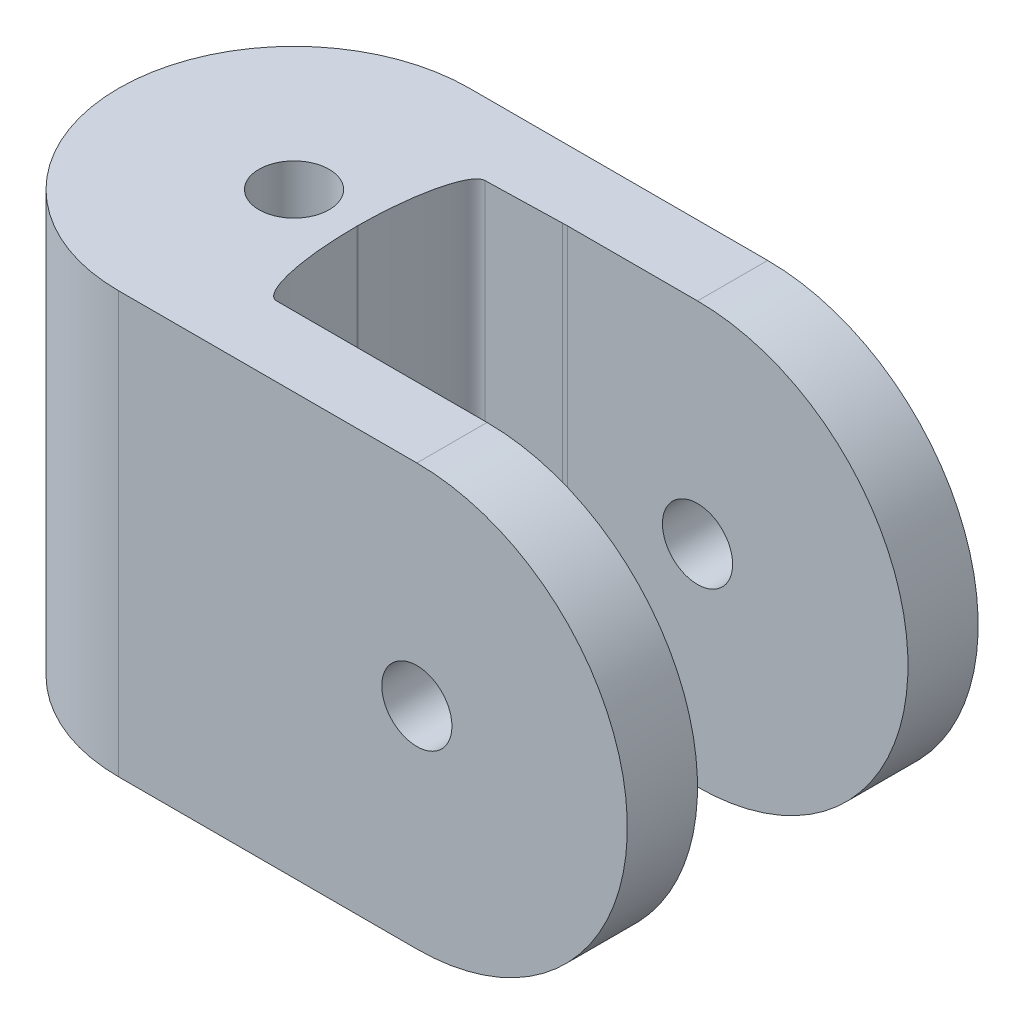
SolidWorks part; units mm, degrees
ref_plane "Front Plane" through (0, 0, 0) normal (0, 0, 1) x (1, 0, 0)
ref_plane "Top Plane" through (0, 0, 0) normal (0, 1, 0) x (1, 0, 0)
ref_plane "Right Plane" through (0, 0, 0) normal (1, 0, 0) x (0, 0, -1)
sketch "Sketch1" plane through (0, 0, 0) normal (0, 1, 0) x (1, 0, 0)
  circle A0 centre (0, 0) radius 125
  circle A1 centre (0, 0) radius 25
  dimension "D1" = 250
extrude "Boss-Extrude1" add sketch "Sketch1" along normal blind 300
ref_plane "Plane1" through (0, 0, 0) normal (0, 0, 1) x (1, 0, 0)
sketch "Sketch2" plane through (0, 0, 0) normal (0, 0, 1) x (1, 0, 0)
  line L0 (0, 300) -> (0, 0) construction
  line L1 (125, 300) -> (-125, 300) construction
  line L2 (0, 300) -> (425, 300) construction
  line L3 (425, 300) -> (425, 0) construction
  line L4 (425, 0) -> (0, 0) construction
  line L5 (0, 150) -> (425, 150) construction
  line L6 (0, 300) -> (0, 0)
  line L7 (0, 300) -> (212.5, 300)
  line L8 (0, 0) -> (212.5, 0)
  circle A0 centre (212.5, 150) radius 25
  arc A1 (212.5, 0) -> (212.5, 300) centre (212.5, 150) ccw
  dimension "D1" = 425
extrude "Boss-Extrude2" add sketch "Sketch2" along normal mid plane 250
sketch "Sketch4" plane through (0, 0, 0) normal (0, 0, 1) x (1, 0, 0)
  line L0 (0, 300) -> (0, 0)
  line L1 (0, 0) -> (212.5, 0)
  line L2 (0, 300) -> (212.5, 300)
  line L3 (3.7723, 300) -> (3.7723, 0)
  line L4 (3.7723, 0) -> (150, 0)
  line L5 (3.7723, 300) -> (150, 300)
  arc A0 (212.5, 0) -> (212.5, 300) centre (212.5, 150) ccw construction
  arc A1 (212.5, 0) -> (212.5, 300) centre (212.5, 150) ccw
  arc A2 (150, 0) -> (150, 300) centre (212.5, 150) ccw
extrude "Cut-Extrude2" cut sketch "Sketch4" against normal mid plane 150 contours L4 A2 A1 L2 L3
ref_plane "Plane2" through (0, 0, 0) normal (0, 1, 0) x (1, 0, 0)
sketch "Sketch5" plane through (0, 0, 0) normal (0, 1, 0) x (1, 0, 0)
  line L0 (-165, 0) -> (165, 0) construction
  line L1 (3.7723, 75) -> (3.7723, -75)
  line L2 (3.7723, -75) -> (120, -75)
  line L3 (3.7723, 75) -> (120, 75)
  circle A0 centre (0, 0) radius 25
  arc A1 (120, 75) -> (120, -75) centre (120, 0) ccw
  dimension "D1" = 120
extrude "Boss-Extrude3" add sketch "Sketch5" along normal through all contours A1 L3 L1 A0 L2
sketch "Sketch6" plane through (0, 300, 0) normal (0, 1, 0) x (1, 0, 0)
  circle A0 centre (0, 0) radius 25
extrude "Cut-Extrude3" cut sketch "Sketch6" against normal through all
sketch "Sketch9" plane through (0, 0, 0) normal (0, 1, 0) x (1, 0, 0)
  line L0 (120, 75) -> (362.5, 75) construction
  line L1 (212.5, 100) -> (120, 100) construction
  line L2 (212.5, 75) -> (212.5, 125) construction
  dimension "D1" = 242.5
sketch "Sketch10" plane through (0, 0, 0) normal (0, 1, 0) x (1, 0, 0)
  line L0 (62.5, 73.5623) -> (62.5, -75) construction
  line L1 (62.5, -0.7188) -> (62.5, 73.5623) construction
  line L2 (212.5, 75) -> (212.5, -75) construction
  line L3 (62.5, 73.5623) -> (120, 75)
  line L4 (120, 75) -> (120, -75)
  line L5 (120, -75) -> (62.5, -75)
  ellipse E0 centre (62.5, -0.7188) end of major axis (62.5, 73.5623) minor radius 17.5 (62.5, 73.5623) -> (62.5, -75) ccw
extrude "Cut-Extrude4" cut sketch "Sketch10" along normal through all both and the other way through all contours L3 E0 L5 L4
sketch "Sketch11" plane through (0, 0, 0) normal (0, 0, 1) x (1, 0, 0)
  circle A0 centre (212.5, 150) radius 150 construction
